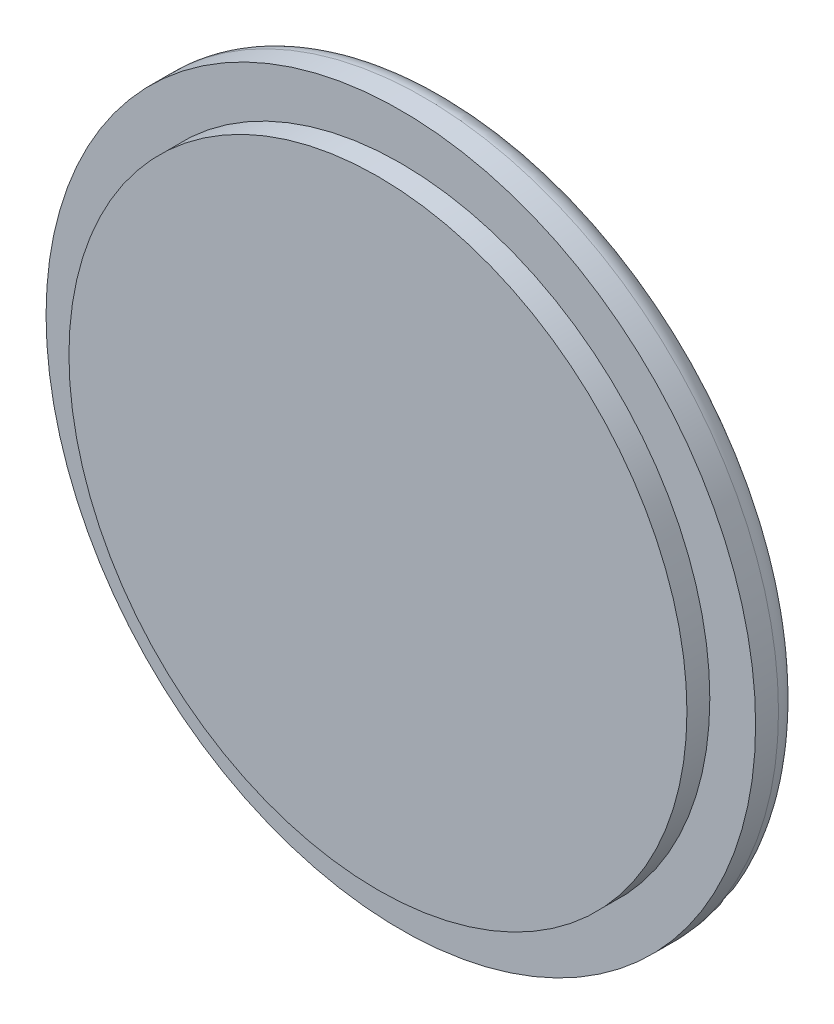
SolidWorks part; units mm, degrees
ref_plane "Ön Düzlem" through (0, 0, 0) normal (0, 0, 1) x (1, 0, 0)
ref_plane "Üst Düzlem" through (0, 0, 0) normal (0, 1, 0) x (1, 0, 0)
ref_plane "Sağ Düzlem" through (0, 0, 0) normal (1, 0, 0) x (0, 0, -1)
sketch "Sketch1" plane through (0, 0, 0) normal (1, 0, 0) x (0, 0, -1)
  line L0 (0, 0) -> (0, 135)
  line L1 (0, 135) -> (10, 135)
  line L2 (10, 135) -> (10, 155)
  line L3 (10, 155) -> (20, 155)
  line L4 (30, 145) -> (30, 0)
  line L5 (30, 0) -> (0, 0)
  arc A0 (30, 145) -> (20, 155) centre (20, 145) ccw
  point P9 (30, 155)
  dimension "D5" = 10
  dimension "D1" = 135
  dimension "D2" = 10
  dimension "D3" = 20
  dimension "D4" = 20
revolve "Revolve1" add sketch "Sketch1" angle 360 about L5
